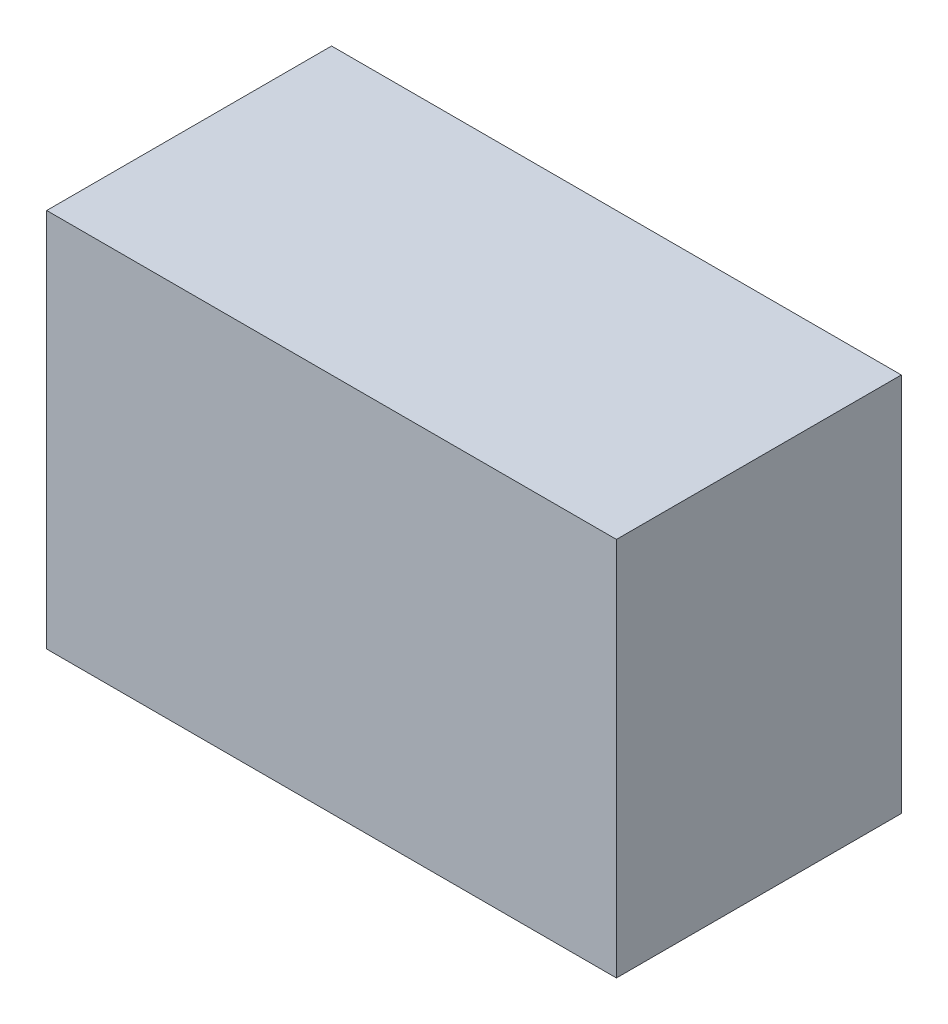
SolidWorks part; units mm, degrees
ref_plane "正面" through (0, 0, 0) normal (0, 0, 1) x (1, 0, 0)
ref_plane "平面" through (0, 0, 0) normal (0, 1, 0) x (1, 0, 0)
ref_plane "右側面" through (0, 0, 0) normal (1, 0, 0) x (0, 0, -1)
sketch "ｽｹｯﾁ1" plane through (0, 0, 0) normal (0, 0, 1) x (1, 0, 0)
  line L1 (0, 0) -> (6, 0)
  line L2 (0, 0) -> (0, 4)
  line L3 (0, 4) -> (6, 4)
  line L4 (6, 0) -> (6, 4)
  dimension "D1" = 4
  dimension "D2" = 6
extrude "ﾎﾞｽ - 押し出し1" add sketch "ｽｹｯﾁ1" along normal blind 3
